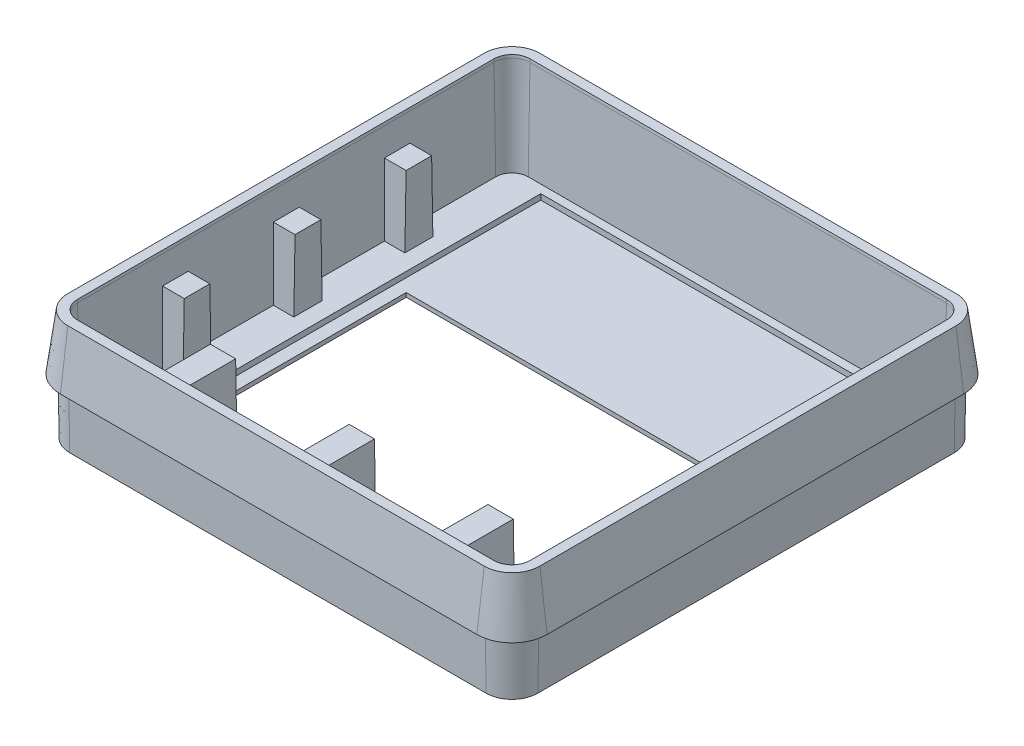
SolidWorks part; units mm, degrees
material "ABS"
ref_plane "Front Plane" through (0, 0, 0) normal (0, 0, 1) x (1, 0, 0)
ref_plane "Top Plane" through (0, 0, 0) normal (0, 1, 0) x (1, 0, 0)
ref_plane "Right Plane" through (0, 0, 0) normal (1, 0, 0) x (0, 0, -1)
sketch "Sketch1" plane through (0, 0, 0) normal (0, 1, 0) x (1, 0, 0)
  line L1 (-7.5, -8.5) -> (7.5, -8.5)
  line L2 (-8.5, -7.5) -> (-8.5, 7.5)
  line L3 (-7.5, 8.5) -> (7.5, 8.5)
  line L4 (8.5, -7.5) -> (8.5, 7.5)
  line L5 (-8.5, -8.5) -> (8.5, 8.5) construction
  line L6 (-8.5, 8.5) -> (8.5, -8.5) construction
  arc A0 (-8.5, 7.5) -> (-7.5, 8.5) centre (-7.5, 7.5) cw
  arc A1 (8.5, 7.5) -> (7.5, 8.5) centre (7.5, 7.5) ccw
  arc A2 (8.5, -7.5) -> (7.5, -8.5) centre (7.5, -7.5) cw
  arc A3 (-7.5, -8.5) -> (-8.5, -7.5) centre (-7.5, -7.5) cw
  point P0 (0, 0)
  dimension "D3" = 1
  dimension "D1" = 17
  dimension "D2" = 17
extrude "Boss-Extrude1" add sketch "Sketch1" against normal blind 4 draft 1
shell "Shell1" thickness 0.35
sketch "Sketch2" plane through (0, -4, 0) normal (0, -1, 0) x (1, 0, 0)
  line L0 (-7.5, 8.5) -> (7.5, 8.5) construction
  line L1 (-6.29, 4.5) -> (6.29, 4.5)
  line L2 (-6.29, 4.5) -> (-6.29, -2.48)
  line L3 (-6.29, -2.48) -> (6.29, -2.48)
  line L4 (6.29, 4.5) -> (6.29, -2.48)
  point P0 (0, 0)
  dimension "D1" = 4
  dimension "D2" = 6.98
extrude "Cut-Extrude1" cut sketch "Sketch2" against normal blind 2
sketch "Sketch3" plane through (0, -3.65, 0) normal (0, 1, 0) x (1, 0, 0)
  line L1 (6.75, 7.7862) -> (-6.75, 7.7862)
  line L2 (6.75, 7.7862) -> (6.75, -5.31)
  line L3 (6.75, -5.31) -> (-6.75, -5.31)
  line L4 (-6.75, 7.7862) -> (-6.75, -5.31)
  line L5 (6.29, 2.48) -> (6.29, -4.5) construction
  line L6 (-6.29, -4.5) -> (-6.29, 2.48) construction
  line L8 (6.29, -4.5) -> (-6.29, -4.5) construction
  line L9 (7.5, 8.0862) -> (-7.5, 8.0862) construction
  point P0 (0, 0)
  dimension "D1" = 0.81
  dimension "D2" = 0.46
  dimension "D3" = 0.46
  dimension "D4" = 0.3
extrude "Cut-Extrude2" cut sketch "Sketch3" against normal blind 0.2
ref_plane "Plane1" through (0, -1.2, 0) normal (0, -1, 0) x (-1, 0, 0)
ref_plane "Plane4" through (7.35, 0, 0) normal (-1, 0, 0) x (0, 0, 1)
sketch "Sketch11" plane through (7.35, 0, 0) normal (-1, 0, 0) x (0, 0, 1)
  line L0 (-9.35, -1.2) -> (9.35, -1.2) construction
  line L1 (-0.4555, -1.1) -> (0.4651, -1.1)
  line L3 (-0.5, -3.65) -> (0.5096, -3.65)
  line L5 (-7.5, -3.65) -> (7.5, -3.65) construction
  line L7 (0.5096, -3.65) -> (0.4651, -1.1)
  line L8 (-0.5, -3.65) -> (-0.4555, -1.1)
  dimension "D1" = 0.1
  dimension "D2" = 89
  dimension "D3" = 89
extrude "Boss-Extrude3" add sketch "Sketch11" against normal up to surface (0.7362 mm away)
ref_plane "Plane5" through (-7.35, 0, 0) normal (1, 0, 0) x (0, 0, -1)
sketch "Sketch13" plane through (-7.35, 0, 0) normal (1, 0, 0) x (0, 0, -1)
  line L0 (-9.35, -1.2) -> (9.35, -1.2) construction
  line L3 (-0.5, -3.65) -> (0.5096, -3.65)
  line L6 (0.5096, -3.65) -> (0.4651, -1.1)
  line L7 (-0.5, -3.65) -> (-0.4555, -1.1)
  line L8 (-0.4555, -1.1) -> (0.4651, -1.1)
  dimension "D1" = 0.1
  dimension "D2" = 89
  dimension "D3" = 89
extrude "Boss-Extrude4" add sketch "Sketch13" against normal up to surface (0.7362 mm away)
ref_plane "Plane6" through (0, 0, 0) normal (1, 0, 0.0016) x (0.0016, 0, -1)
pattern_linear "LPattern2" count 2 spacing 4 along (0, 0, 1) of "Boss-Extrude3"
mirror "Mirror4" about plane through (0, 0, 0) normal (0, 0, 1) of "LPattern2", "Boss-Extrude3"
pattern_linear "LPattern3" count 2 spacing 4 along (0, 0, 1) of "Boss-Extrude4"
mirror "Mirror5" about plane through (0, 0, 0) normal (0, 0, 1) of "LPattern3", "Boss-Extrude4"
ref_plane "Plane7" through (0, 0, 5.41) normal (0, 0, 1) x (1, 0, 0)
sketch "Sketch16" plane through (0, 0, 5.41) normal (0, 0, 1) x (1, 0, 0)
  line L0 (-0.5, -3.65) -> (0.5, -3.65)
  line L1 (-7.5, -3.65) -> (7.5, -3.65) construction
  line L2 (0, -55) -> (0, 55) construction
  line L3 (-0.4555, -1.1) -> (0.4555, -1.1)
  line L5 (-0.5, -3.65) -> (-0.4555, -1.1)
  line L6 (0.5, -3.65) -> (0.4555, -1.1)
  line L7 (-9.35, -1.2) -> (9.35, -1.2) construction
  point P9 (0, -1.1)
  dimension "D1" = 0.5
  dimension "D2" = 0.5
  dimension "D3" = 89
  dimension "D4" = 89
  dimension "D5" = 0.1
extrude "Boss-Extrude5" add sketch "Sketch16" along normal up to surface (2.6762 mm away)
pattern_linear "LPattern4" count 2 spacing 5 along (1, 0, 0) of "Boss-Extrude5"
mirror "Mirror6" about plane through (0, 0, 0) normal (1, 0, 0) of "LPattern4"
sketch "Sketch17" plane through (0, 0, 0) normal (0, 0, 1) x (1, 0, 0)
  line L0 (-8.5, 0) -> (-8.4651, -2)
  line L1 (9.35, 0) -> (-9.35, 0) construction
  line L2 (-8.4302, -4) -> (-8.5, 0) construction
  line L3 (-8.4651, -2) -> (-8.7651, -2)
  line L4 (-8.7651, -2) -> (-8.5, 0)
  line L5 (-8.4302, -4) -> (-7.5, -4) construction
  dimension "D1" = 0.3
  dimension "D2" = 2
ref_plane "Plane8" through (0, -2, 0) normal (0, -1, 0) x (-1, 0, 0)
sketch "Sketch18" plane through (0, -2, 0) normal (0, -1, 0) x (-1, 0, 0)
  line L0 (8.5, 7.5) -> (8.5, -7.5) construction
  line L1 (7.5, -8.5) -> (-7.5, -8.5) construction
  line L2 (-8.5, -7.5) -> (-8.5, 7.5) construction
  line L3 (-7.5, 8.5) -> (7.5, 8.5) construction
  line L4 (8.5, 7.5) -> (8.5, -7.5)
  line L5 (7.5, -8.5) -> (-7.5, -8.5)
  line L6 (-8.5, -7.5) -> (-8.5, 7.5)
  line L7 (-7.5, 8.5) -> (7.5, 8.5)
  arc A0 (8.5, 7.5) -> (7.5, 8.5) centre (7.5, 7.5) ccw construction
  arc A1 (7.5, -8.5) -> (8.5, -7.5) centre (7.5, -7.5) ccw construction
  arc A2 (-8.5, -7.5) -> (-7.5, -8.5) centre (-7.5, -7.5) ccw construction
  arc A3 (-7.5, 8.5) -> (-8.5, 7.5) centre (-7.5, 7.5) ccw construction
  arc A4 (8.5, 7.5) -> (7.5, 8.5) centre (7.5, 7.5) ccw
  arc A5 (7.5, -8.5) -> (8.5, -7.5) centre (7.5, -7.5) ccw
  arc A6 (-8.5, -7.5) -> (-7.5, -8.5) centre (-7.5, -7.5) ccw
  arc A7 (-7.5, 8.5) -> (-8.5, 7.5) centre (-7.5, 7.5) ccw
sweep "Sweep1" add profiles "Sketch17" path "Sketch18"
sketch "Sketch19" plane through (0, 0, 0) normal (0, 0, 1) x (1, 0, 0)
  line L0 (8.1499, 0) -> (8.1482, -0.1025)
  line L1 (9.6416, 0) -> (-9.6416, 0) construction
  line L2 (8.0862, -3.65) -> (8.1499, 0) construction
  line L3 (8.1499, 0) -> (8.141, -0.1025)
  line L4 (8.141, -0.1025) -> (8.1482, -0.1025)
  dimension "D1" = 85
  dimension "D2" = 0.1025
sketch "Sketch23" plane through (0, 0, 0) normal (0, 1, 0) x (1, 0, 0)
  line L0 (8.1499, -7.5) -> (8.1499, 7.5) construction
  line L1 (-7.5, -8.1499) -> (7.5, -8.1499) construction
  line L2 (7.5, 8.1499) -> (-7.5, 8.1499) construction
  line L3 (-8.1499, 7.5) -> (-8.1499, -7.5) construction
  line L4 (8.1499, -7.5) -> (8.1499, 7.5)
  line L5 (-7.5, -8.1499) -> (7.5, -8.1499)
  line L6 (7.5, 8.1499) -> (-7.5, 8.1499)
  line L7 (-8.1499, 7.5) -> (-8.1499, -7.5)
  arc A0 (8.1499, 7.5) -> (7.5, 8.1499) centre (7.5, 7.5) ccw construction
  arc A1 (7.5, -8.1499) -> (8.1499, -7.5) centre (7.5, -7.5) ccw construction
  arc A2 (-8.1499, -7.5) -> (-7.5, -8.1499) centre (-7.5, -7.5) ccw construction
  arc A3 (-7.5, 8.1499) -> (-8.1499, 7.5) centre (-7.5, 7.5) ccw construction
  arc A4 (8.1499, 7.5) -> (7.5, 8.1499) centre (7.5, 7.5) ccw
  arc A5 (7.5, -8.1499) -> (8.1499, -7.5) centre (7.5, -7.5) ccw
  arc A6 (-8.1499, -7.5) -> (-7.5, -8.1499) centre (-7.5, -7.5) ccw
  arc A7 (-7.5, 8.1499) -> (-8.1499, 7.5) centre (-7.5, 7.5) ccw
sweep "Sweep2" add profiles "Sketch19" path "Sketch23"
